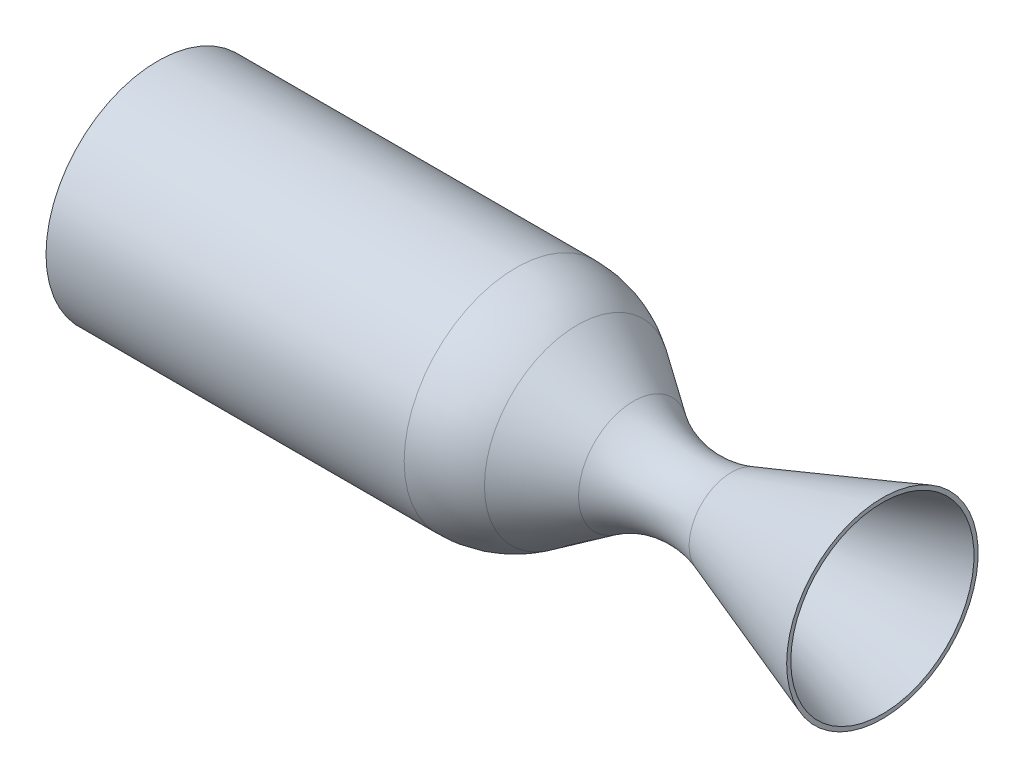
SolidWorks part; units mm, degrees
ref_plane "Front Plane" through (0, 0, 0) normal (0, 0, 1) x (1, 0, 0)
ref_plane "Top Plane" through (0, 0, 0) normal (0, 1, 0) x (1, 0, 0)
ref_plane "Right Plane" through (0, 0, 0) normal (1, 0, 0) x (0, 0, -1)
sketch "Sketch1" plane through (0, 0, 0) normal (0, 0, 1) x (1, 0, 0)
  line L0 (0, 0) -> (182.8441, 0)
  line L1 (214.2119, -9.6097) -> (242.8614, -28.9817)
  line L2 (292.9126, -35.3828) -> (369.9692, -8.1117)
  line L3 (0, -2) -> (182.8441, -2)
  line L4 (213.0916, -11.2665) -> (241.7411, -30.6385)
  line L5 (293.5798, -37.2682) -> (369.9692, -10.2332)
  line L6 (0, 0) -> (0, -2)
  line L8 (0, -57) -> (404.6809, -57) construction
  line L9 (369.9692, -8.1117) -> (369.9692, -10.2332)
  line L10 (293.5798, -37.2682) -> (370.6365, -9.9971) construction
  arc A0 (242.8614, -28.9817) -> (292.9126, -35.3828) centre (274.2292, 17.4086) ccw
  arc A1 (182.8441, 0) -> (214.2119, -9.6097) centre (182.8441, -56) cw
  arc A2 (182.8441, -2) -> (213.0916, -11.2665) centre (182.8441, -56) cw
  arc A3 (241.7411, -30.6385) -> (293.5798, -37.2682) centre (274.2292, 17.4086) ccw
  point P7 (266.2719, -44.8112)
  point P10 (200, 0)
  dimension "D4" = 56
  dimension "D1" = 200
  dimension "D2" = 80
  dimension "D3" = 110
  dimension "D6" = 55
  dimension "D5" = 2
revolve "Revolve1" add sketch "Sketch1" angle 360 about L8
sketch "Sketch2" plane through (0, 0, 0) normal (-1, 0, 0) x (0, 0, 1)
  line L0 (-0.5, 0.0022) -> (0.5, -0.0022)
  line L1 (0.5, -0.0022) -> (0.5, 0.9978)
  line L2 (0.5, 0.9978) -> (-0.5, 0.9978)
  line L3 (-0.5, 0.9978) -> (-0.5, 0.0022)
  circle A0 centre (0, -57) radius 57 construction
  point P6 (0, 0)
sketch "Sketch3" plane through (369.9692, 0, 0) normal (1, 0, 0) x (0, 0, -1)
  line L0 (0, -57) -> (0, -8.1117)
  line L1 (0, -57) -> (-36.9313, -4.2566)
  line L2 (-0.5, -8.1091) -> (0.5, -8.1142)
  line L3 (0.5, -8.1142) -> (0.5, -7.1142)
  line L4 (0.5, -7.1142) -> (-0.5, -7.1142)
  line L5 (-0.5, -7.1142) -> (-0.5, -8.1091)
  line L6 (-29.0229, -16.4228) -> (-28.4522, -17.2377)
  line L7 (-28.2037, -15.8492) -> (-29.0229, -16.4228)
  line L8 (-27.6301, -16.6683) -> (-28.2037, -15.8492)
  line L9 (-28.4522, -17.2377) -> (-27.6301, -16.6683)
  circle A0 centre (0, -57) radius 48.8883 construction
  point P10 (0, -8.1117)
  point P19 (0, -57)
  dimension "D1" = 35
  dimension "D2" = 1
  dimension "D3" = 1
  dimension "D4" = 2
sketch3d "3DSketch2"
  circle A0 centre (0, -57, 0) radius 57 construction
  circle A1 centre (242.8614, -57, 0) radius 28.0183 construction
  circle A2 centre (242.8614, -57, 0) radius 28.0183 construction
  circle A3 centre (369.9692, -57, 0) radius 48.8883 construction
  point P0 (0, 0, 0)
  point P1 (214.2119, -15.6238, 23.1052)
  point P4 (-57, -57, 0)
  point P5 (242.8614, -35.0554, 17.4201)
  point P8 (214.8431, -57, 0)
  point P9 (369.9692, -16.953, 28.0412)
  point P12 (214.8431, -57, 0)
  point P15 (321.0809, -57, 0)
ref_plane "Plane2" through (250, 0, 0) normal (-1, 0, 0) x (0, 0, 1)
sketch "Sketch6" plane through (250, 0, 0) normal (-1, 0, 0) x (0, 0, 1)
  circle A0 centre (0, -57) radius 57
  point P4 (0, -57)
  point P5 (0, 0)
ref_plane "Plane1" through (0, 0, 0) normal (-0.0872, -0.3827, 0.9198) x (0.9962, -0.0335, 0.0806)
sketch "Sketch11" plane through (0, 0, 0) normal (-0.0872, -0.3827, 0.9198) x (0.9962, -0.0335, 0.0806)
  line L0 (0, 10.6671) -> (384.5745, 10.6671)
ref_plane "Plane3" through (0, -48.5896, -20.2153) normal (0, -0.9233, -0.3841) x (1, 0, 0)
ref_plane "Plane4" through (0, 43.7386, 18.1971) normal (0, 0.9233, 0.3841) x (-1, 0, 0)
